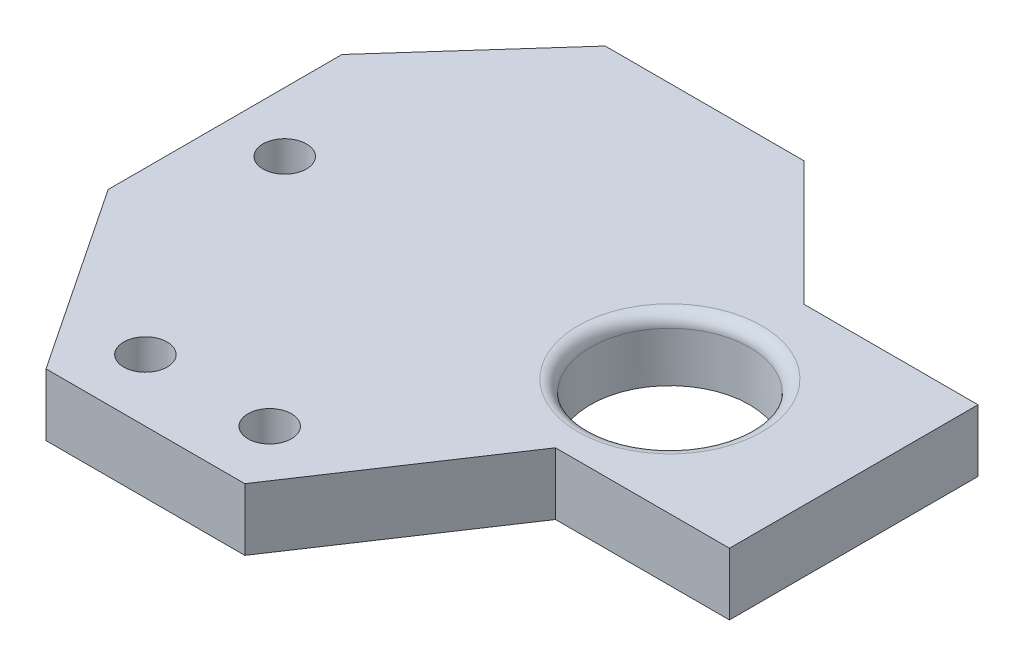
SolidWorks part; units mm, degrees
ref_plane "Front Plane" through (0, 0, 0) normal (0, 0, 1) x (1, 0, 0)
ref_plane "Top Plane" through (0, 0, 0) normal (0, 1, 0) x (1, 0, 0)
ref_plane "Right Plane" through (0, 0, 0) normal (1, 0, 0) x (0, 0, -1)
sketch "Sketch1" plane through (0, 0, 0) normal (0, 1, 0) x (1, 0, 0)
  line L0 (0, 33.8197) -> (10, 45)
  line L1 (0, 0) -> (50, 0)
  line L2 (0, 0) -> (0, 45)
  line L3 (0, 45) -> (50, 45)
  line L4 (50, 0) -> (50, 45)
  line L5 (0, 15) -> (10, 0)
  line L6 (26, 45) -> (36, 35)
  line L7 (26, 0) -> (36, 15)
  line L8 (36, 15) -> (50, 15)
  line L9 (36, 35) -> (50, 35)
  line L10 (50, 25) -> (0, 25) construction
  circle A1 centre (13, 5) radius 1.75
  circle A2 centre (23, 5) radius 1.75
  dimension "D15" = 10
  dimension "D16" = 3.5
  dimension "D24" = 3
  dimension "D25" = 3
  dimension "D17" = 3.5
  dimension "D1" = 45
  dimension "D2" = 50
  dimension "D3" = 15
  dimension "D4" = 10
  dimension "D5" = 10
  dimension "D6" = 15
  dimension "D7" = 16
  dimension "D8" = 16
  dimension "D9" = 10
  dimension "D10" = 10
  dimension "D11" = 10
  dimension "D12" = 20
  dimension "D13" = 10
  dimension "D18" = 5
extrude "Boss-Extrude1" add sketch "Sketch1" along normal blind 5
ref_plane "Plane1" through (0, 0, 0) normal (0, -1, 0) x (-1, 0, 0)
sketch "Sketch2" plane through (0, 0, 0) normal (0, -1, 0) x (-1, 0, 0)
  line L0 (0, 24.4098) -> (-68.9029, 24.4098) construction
  line L1 (0, 15) -> (0, 33.8197) construction
  circle A0 centre (-4.8, 24.4098) radius 1.75
  circle A1 centre (-35.8, 24.4098) radius 6.4
  dimension "D1" = 4.8
  dimension "D2" = 12.8
  dimension "D3" = 31
extrude "Cut-Extrude1" cut sketch "Sketch2" against normal blind 10
fillet "Fillet1" radius 1 1 edges at (35.8, 5, -18.0098)
